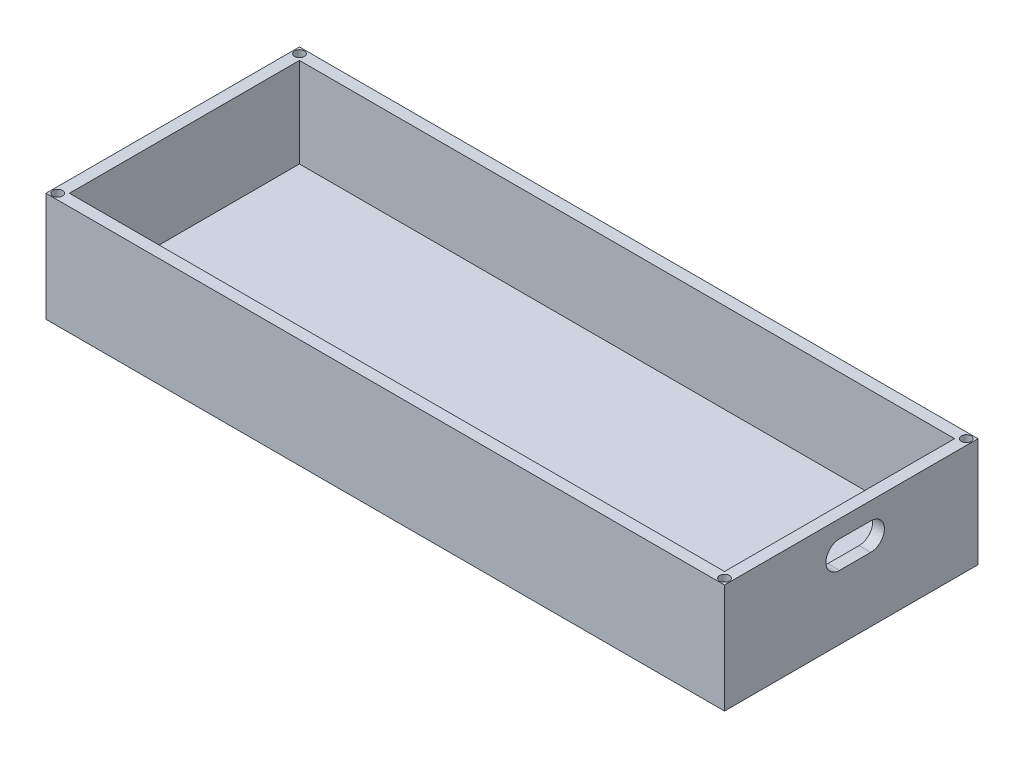
SolidWorks part; units mm, degrees
ref_plane "Front Plane" through (0, 0, 0) normal (0, 0, 1) x (1, 0, 0)
ref_plane "Top Plane" through (0, 0, 0) normal (0, 1, 0) x (1, 0, 0)
ref_plane "Right Plane" through (0, 0, 0) normal (1, 0, 0) x (0, 0, -1)
sketch "Sketch1" plane through (0, 0, 0) normal (0, 1, 0) x (1, 0, 0)
  line L1 (-87, -32.5) -> (87, -32.5)
  line L2 (-87, -32.5) -> (-87, 32.5)
  line L3 (-87, 32.5) -> (87, 32.5)
  line L4 (87, -32.5) -> (87, 32.5)
  line L5 (-87, -32.5) -> (87, 32.5) construction
  line L6 (-87, 32.5) -> (87, -32.5) construction
  point P0 (0, 0)
  dimension "D1" = 65
  dimension "D2" = 174
extrude "Boss-Extrude1" add sketch "Sketch1" along normal blind 5
sketch "Sketch2" plane through (0, 5, 0) normal (0, 1, 0) x (1, 0, 0)
  line L0 (-84, -29.5) -> (-84, 29.5)
  line L1 (-87, -32.5) -> (87, -32.5)
  line L2 (-87, -32.5) -> (-87, 32.5)
  line L3 (-87, 32.5) -> (87, 32.5)
  line L4 (87, -32.5) -> (87, 32.5)
  line L5 (-84, 29.5) -> (84, 29.5)
  line L6 (84, -29.5) -> (84, 29.5)
  line L7 (-84, -29.5) -> (84, -29.5)
  dimension "D1" = 3
extrude "Boss-Extrude2" add sketch "Sketch2" along normal blind 23
sketch "Sketch3" plane through (87, 0, 0) normal (1, 0, 0) x (0, 0, -1)
  line L0 (-32.5, 28) -> (-32.5, 0) construction
  line L3 (-3, 20) -> (5, 20) construction
  line L4 (-3, 23.5) -> (5, 23.5)
  line L5 (-3, 16.5) -> (5, 16.5)
  line L7 (-32.5, 0) -> (32.5, 0) construction
  arc A0 (-3, 23.5) -> (-3, 16.5) centre (-3, 20) ccw
  arc A1 (5, 16.5) -> (5, 23.5) centre (5, 20) ccw
  point P8 (1, 20)
  dimension "D3" = 29.5
  dimension "D1" = 8
  dimension "D2" = 3.5
  dimension "D4" = 16.5
extrude "Cut-Extrude1" cut sketch "Sketch3" against normal blind 23
sketch "Sketch4" plane through (0, 28, 0) normal (0, 1, 0) x (1, 0, 0)
  line L0 (-87, 32.5) -> (-84, 29.5) construction
  circle A0 centre (-85.5, 31) radius 1.25
  circle A1 centre (85.5, 31) radius 1.25
  circle A2 centre (85.5, -31) radius 1.25
  circle A3 centre (-85.5, -31) radius 1.25
  dimension "D1" = 2.5
  dimension "D2" = 2
  dimension "D3" = 2
extrude "Cut-Extrude2" cut sketch "Sketch4" against normal blind 5
